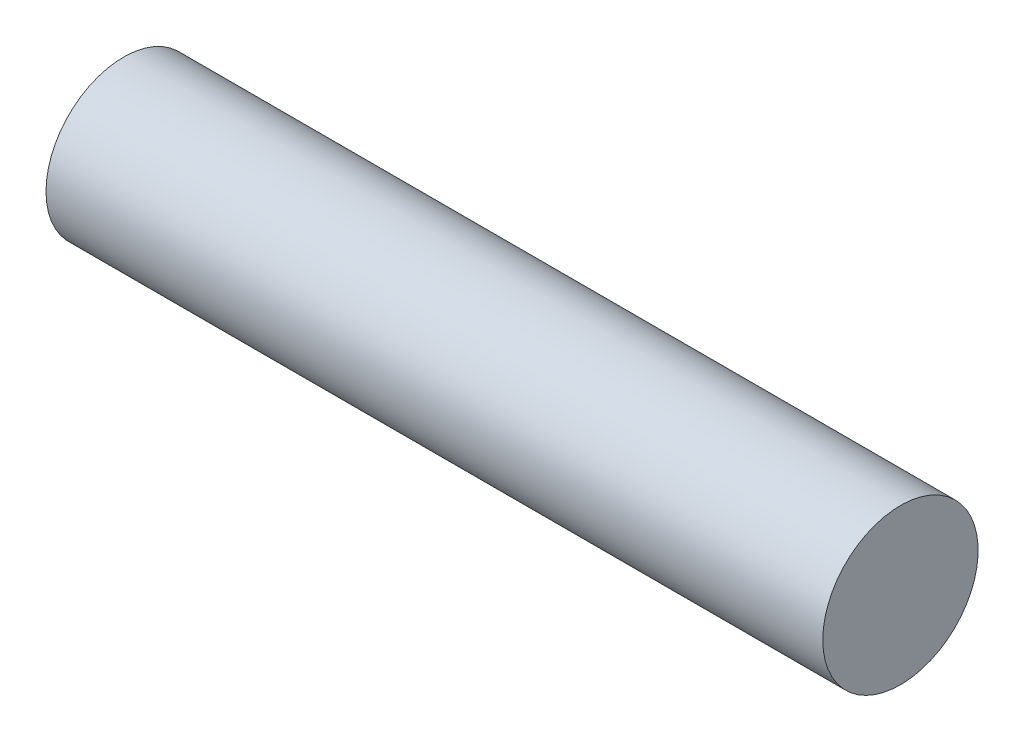
SolidWorks part; units mm, degrees
material "Cast Alloy Steel"
ref_plane "Front" through (0, 0, 0) normal (0, 0, 1) x (1, 0, 0)
ref_plane "Top" through (0, 0, 0) normal (0, 1, 0) x (1, 0, 0)
ref_plane "Right" through (0, 0, 0) normal (1, 0, 0) x (0, 0, -1)
sketch "Sketch1" plane through (0, 0, 0) normal (0, 0, 1) x (1, 0, 0)
  line L1 (-5, 0.5) -> (5, 0.5)
  line L2 (-5, 0.5) -> (-5, -0.5)
  line L3 (-5, -0.5) -> (5, -0.5)
  line L4 (5, 0.5) -> (5, -0.5)
  line L5 (-5, 0.5) -> (5, -0.5) construction
  line L6 (-5, -0.5) -> (5, 0.5) construction
  point P0 (0, 0)
  dimension "D1" = 1
  dimension "D2" = 10
revolve "Revolve1" add sketch "Sketch1" angle 360 about L3
